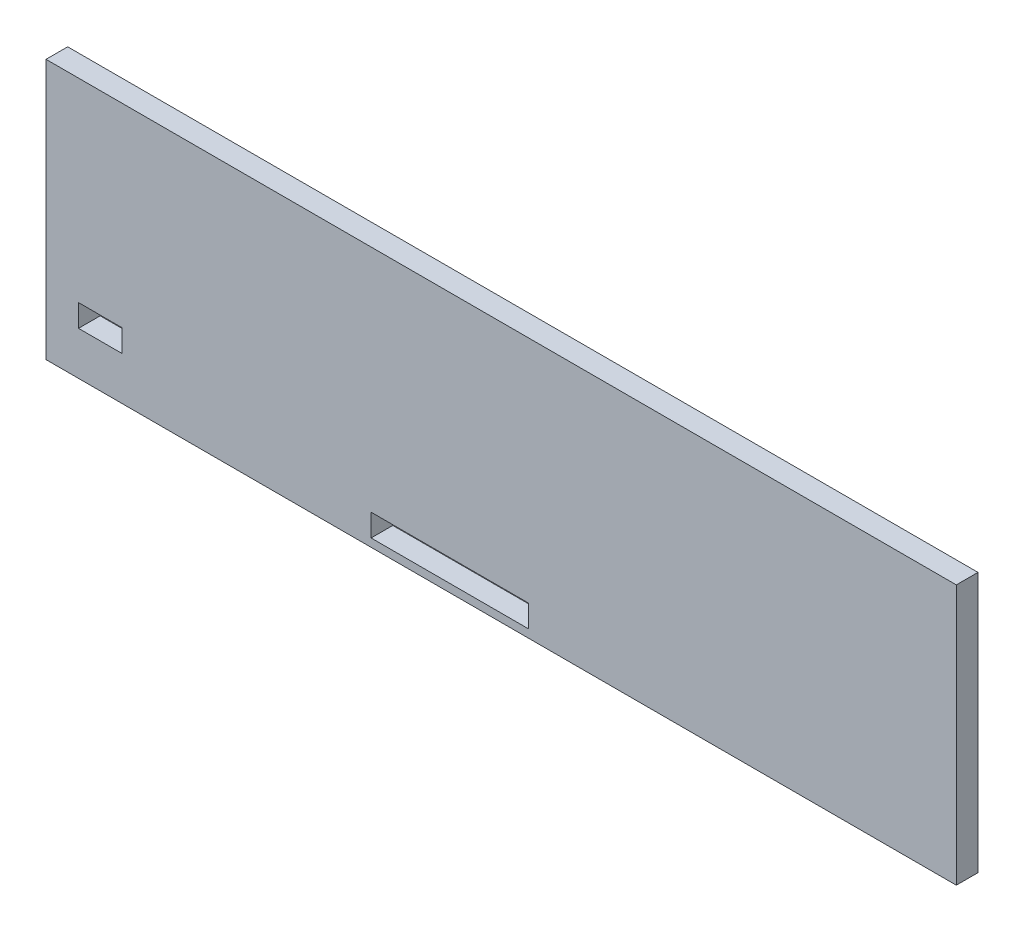
SolidWorks part; units mm, degrees
ref_plane "Front Plane" through (0, 0, 0) normal (0, 0, 1) x (1, 0, 0)
ref_plane "Top Plane" through (0, 0, 0) normal (0, 1, 0) x (1, 0, 0)
ref_plane "Right Plane" through (0, 0, 0) normal (1, 0, 0) x (0, 0, -1)
sketch "Sketch1" plane through (0, 0, 0) normal (0, 0, 1) x (1, 0, 0)
  line L1 (0, 0) -> (533.4, 0)
  line L2 (0, 0) -> (0, 152.4)
  line L3 (0, 152.4) -> (533.4, 152.4)
  line L4 (533.4, 0) -> (533.4, 152.4)
extrude "Boss-Extrude1" add sketch "Sketch1" along normal blind 12.7
sketch "Sketch2" plane through (0, 0, 0) normal (0, 0, 1) x (1, 0, 0)
  line L1 (19.05, 25.4) -> (44.45, 25.4)
  line L2 (19.05, 25.4) -> (19.05, 38.481)
  line L3 (19.05, 38.481) -> (44.45, 38.481)
  line L4 (44.45, 25.4) -> (44.45, 38.481)
extrude "Cut-Extrude1" cut sketch "Sketch2" along normal through all
sketch "Sketch3" plane through (0, 0, 0) normal (0, 0, 1) x (1, 0, 0)
  line L1 (190.5, 4.7498) -> (282.702, 4.7498)
  line L2 (190.5, 4.7498) -> (190.5, 17.8308)
  line L3 (190.5, 17.8308) -> (282.702, 17.8308)
  line L4 (282.702, 4.7498) -> (282.702, 17.8308)
extrude "Cut-Extrude2" cut sketch "Sketch3" along normal through all
